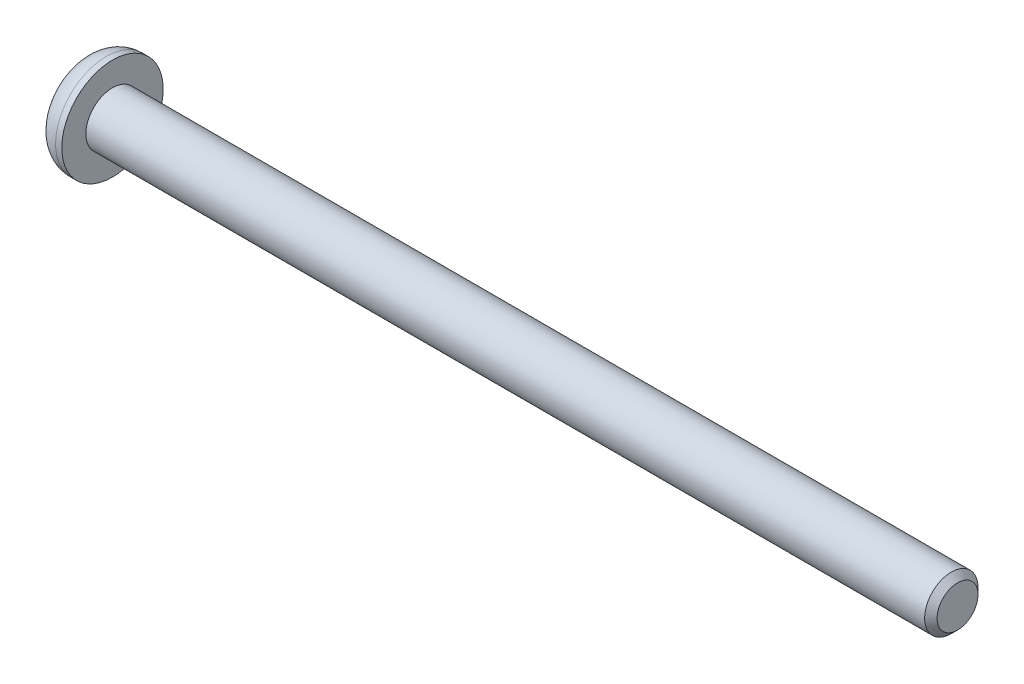
SolidWorks part; units mm, degrees
ref_plane "Ön Düzlem" through (0, 0, 0) normal (0, 0, 1) x (1, 0, 0)
ref_plane "Üst Düzlem" through (0, 0, 0) normal (0, 1, 0) x (1, 0, 0)
ref_plane "Sağ Düzlem" through (0, 0, 0) normal (1, 0, 0) x (0, 0, -1)
sketch "Çizim1" plane through (0, 0, 0) normal (0, 0, 1) x (1, 0, 0)
  line L0 (0, 0) -> (98.3, 0)
  line L1 (0, 0) -> (0, 2.85)
  line L2 (2.6, 5.7) -> (3.3, 5.7)
  line L3 (3.3, 5.7) -> (3.3, 3)
  line L4 (3.3, 3) -> (98.3, 3)
  line L5 (98.3, 3) -> (98.3, 0)
  arc A0 (2.6, 5.7) -> (0, 2.85) centre (2.6, 3.089) ccw
  point P6 (2.95, 5.7)
  dimension "D1" = 95
  dimension "D2" = 3
  dimension "D3" = 5.7
  dimension "D4" = 0.7
  dimension "D5" = 2.85
  dimension "D6" = 3.3
revolve "Döndür1" add sketch "Çizim1" angle 360 about L0
chamfer "Pah1" distance 0.7 angle 45 1 edges at (98.3, -3, 0)
sketch "Çizim2" plane through (0, 0, 0) normal (-1, 0, 0) x (0, 0, 1)
  line L1 (0, 1.6454) -> (-1.425, 0.8227)
  line L2 (-1.425, 0.8227) -> (-1.425, -0.8227)
  line L3 (-1.425, -0.8227) -> (0, -1.6454)
  line L4 (0, -1.6454) -> (1.425, -0.8227)
  line L5 (1.425, -0.8227) -> (1.425, 0.8227)
  line L6 (1.425, 0.8227) -> (0, 1.6454)
  circle A0 centre (0, 0) radius 1.425 construction
  dimension "D1" = 2.85
extrude "Kes-Ekstrüzyon1" cut sketch "Çizim2" against normal blind 1.5
